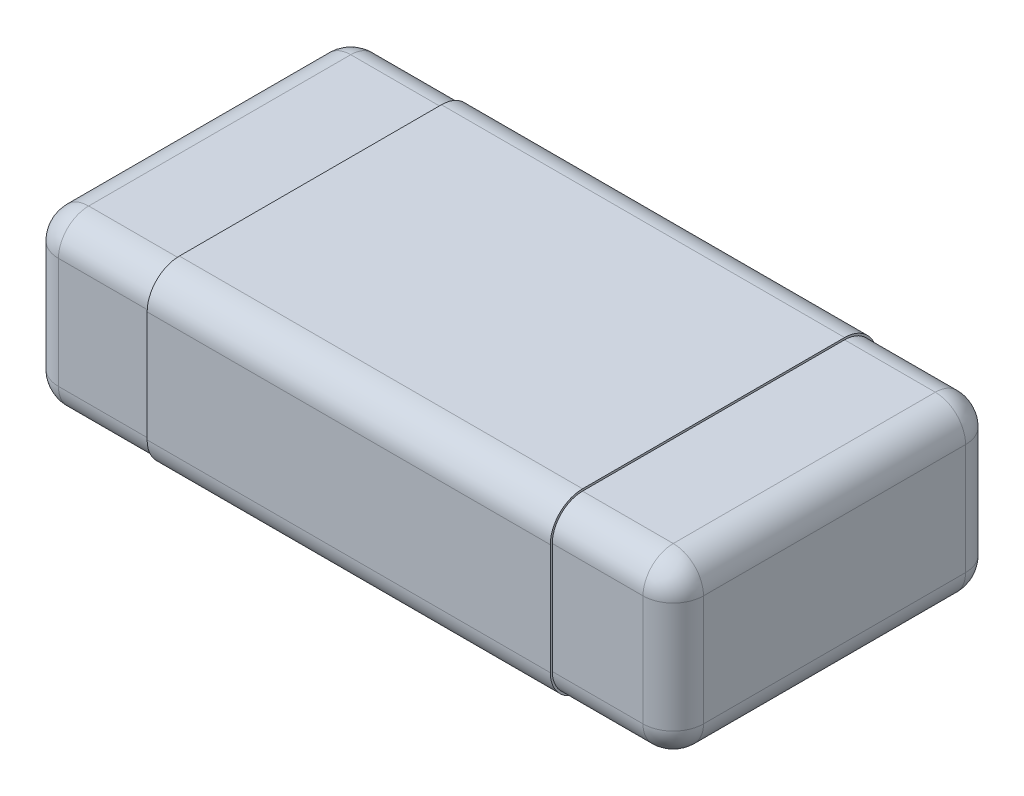
SolidWorks part; units mm, degrees
material "Liga 1060"
ref_plane "Plano frontal" through (0, 0, 0) normal (0, 0, 1) x (1, 0, 0)
ref_plane "Plano superior" through (0, 0, 0) normal (0, 1, 0) x (1, 0, 0)
ref_plane "Plano direito" through (0, 0, 0) normal (1, 0, 0) x (0, 0, -1)
sketch "Esboço1" plane through (0, 0, 0) normal (0, 1, 0) x (1, 0, 0)
  line L0 (-1, -0.625) -> (2.2, -0.625)
  line L1 (2.2, -0.625) -> (2.2, 0.975)
  line L2 (2.2, 0.975) -> (-1, 0.975)
  line L3 (-1, 0.975) -> (-1, -0.625)
  dimension "D1" = 3.2
  dimension "D2" = 1.6
extrude "Ressalto-extrusão1" add sketch "Esboço1" against normal blind 0.85
ref_plane "Plano1" through (0.6, 0, 0) normal (1, 0, 0) x (0, 0, -1)
fillet "Filete1" radius 0.15 12 edges at (0.6, -0.85, -0.975) (-1, -0.425, -0.975) (2.2, -0.425, -0.975) (0.6, 0, -0.975) (-1, -0.85, -0.175) (2.2, -0.85, -0.175) (0.6, -0.85, 0.625) (-1, 0, -0.175) (2.2, 0, -0.175) (-1, -0.425, 0.625) (2.2, -0.425, 0.625) (0.6, 0, 0.625)
sketch "Esboço4" plane through (0.6, 0, 0) normal (1, 0, 0) x (0, 0, -1)
  line L0 (0.975, -0.7) -> (0.975, -0.15) construction
  line L1 (0.975, -0.7) -> (0.975, -0.15)
  line L2 (0.825, -0.85) -> (-0.475, -0.85) construction
  line L3 (0.825, -0.85) -> (-0.475, -0.85)
  line L4 (0.825, 0) -> (-0.475, 0) construction
  line L5 (-0.625, -0.15) -> (-0.625, -0.7) construction
  line L6 (0.825, 0) -> (-0.475, 0)
  line L7 (-0.625, -0.15) -> (-0.625, -0.7)
  line L8 (0.985, -0.7) -> (0.985, -0.15)
  line L9 (0.825, 0.01) -> (-0.475, 0.01)
  line L10 (-0.635, -0.15) -> (-0.635, -0.7)
  line L11 (0.825, -0.86) -> (-0.475, -0.86)
  arc A5 (0.825, -0.85) -> (0.975, -0.7) centre (0.825, -0.7) ccw construction
  arc A6 (0.825, -0.85) -> (0.975, -0.7) centre (0.825, -0.7) ccw
  arc A7 (-0.475, 0) -> (-0.625, -0.15) centre (-0.475, -0.15) ccw construction
  arc A8 (-0.625, -0.7) -> (-0.475, -0.85) centre (-0.475, -0.7) ccw construction
  arc A9 (-0.475, 0) -> (-0.625, -0.15) centre (-0.475, -0.15) ccw
  arc A10 (-0.625, -0.7) -> (-0.475, -0.85) centre (-0.475, -0.7) ccw
  arc A11 (0.975, -0.15) -> (0.825, 0) centre (0.825, -0.15) ccw construction
  arc A12 (0.975, -0.15) -> (0.825, 0) centre (0.825, -0.15) ccw
  arc A13 (0.985, -0.15) -> (0.825, 0.01) centre (0.825, -0.15) ccw
  arc A14 (-0.475, 0.01) -> (-0.635, -0.15) centre (-0.475, -0.15) ccw
  arc A15 (-0.635, -0.7) -> (-0.475, -0.86) centre (-0.475, -0.7) ccw
  arc A16 (0.825, -0.86) -> (0.985, -0.7) centre (0.825, -0.7) ccw
  dimension "D1" = 0.01
extrude "Ressalto-extrusão4" add sketch "Esboço4" along normal blind 1 and the other way blind 1
